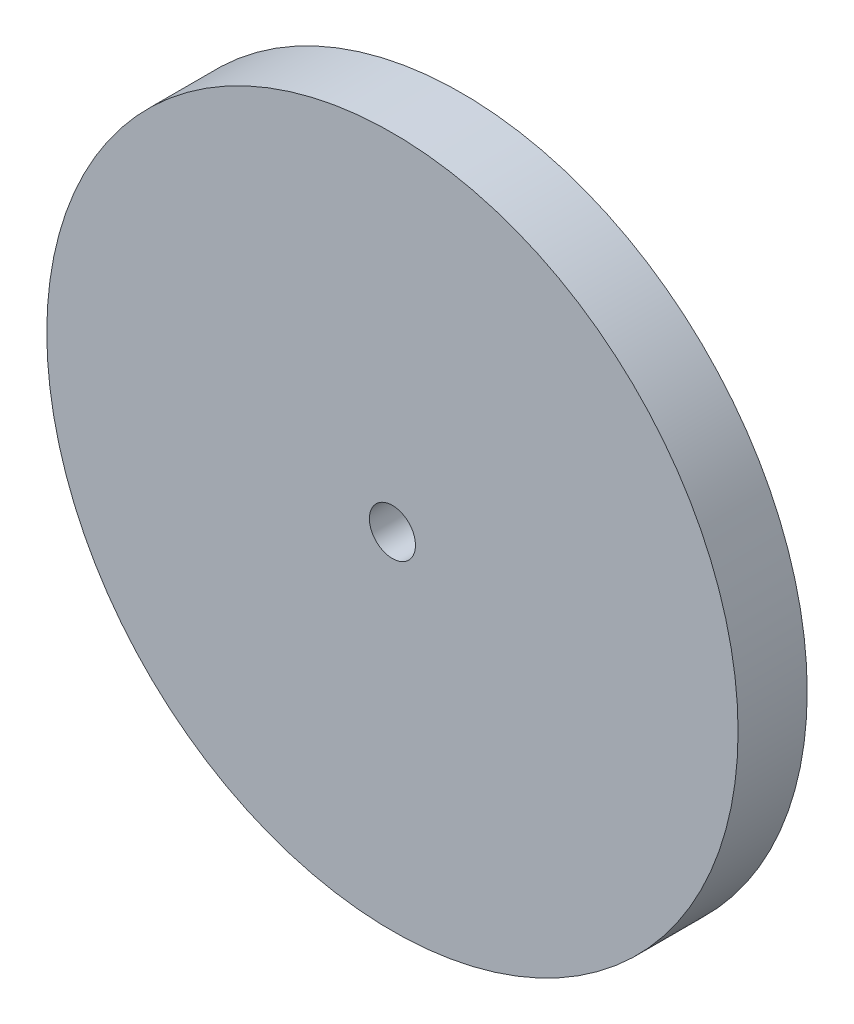
SolidWorks part; units mm, degrees
material "Oak"
ref_plane "Front" through (0, 0, 0) normal (0, 0, 1) x (1, 0, 0)
ref_plane "Top" through (0, 0, 0) normal (0, 1, 0) x (1, 0, 0)
ref_plane "Right" through (0, 0, 0) normal (1, 0, 0) x (0, 0, -1)
sketch "Sketch1" plane through (0, 0, 0) normal (0, 0, 1) x (1, 0, 0)
  circle A0 centre (0, 0) radius 762
  circle A1 centre (0, 0) radius 50.8
  dimension "D1" = 1524
  dimension "D2" = 101.6
extrude "Boss-Extrude1" add sketch "Sketch1" along normal blind 152.4
